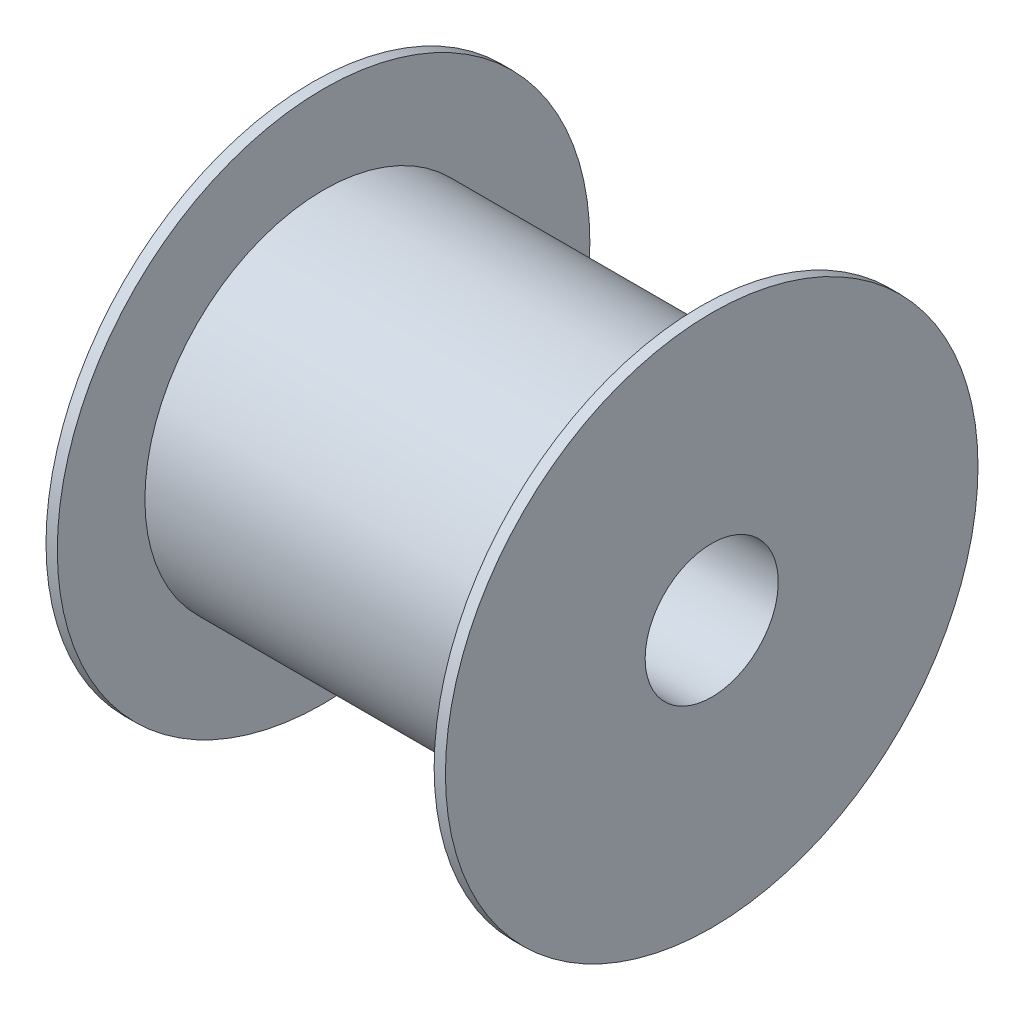
SolidWorks part; units mm, degrees
ref_plane "Front Plane" through (0, 0, 0) normal (0, 0, 1) x (1, 0, 0)
ref_plane "Top Plane" through (0, 0, 0) normal (0, 1, 0) x (1, 0, 0)
ref_plane "Right Plane" through (0, 0, 0) normal (1, 0, 0) x (0, 0, -1)
sketch "Sketch1" plane through (0, 0, 0) normal (0, 0, 1) x (1, 0, 0)
  line L0 (0, 0) -> (0, 10) construction
  line L1 (-30, 10) -> (30, 10)
  line L2 (30, 10) -> (30, 40)
  line L3 (30, 40) -> (28.3029, 40)
  line L4 (28.3029, 40) -> (28.3029, 26.8407)
  line L5 (28.3029, 26.8407) -> (-28.3029, 26.8407)
  line L6 (0, 26.8407) -> (0, 10) construction
  line L7 (-28.3029, 40) -> (-28.3029, 26.8407)
  line L8 (-30, 40) -> (-28.3029, 40)
  line L9 (-30, 10) -> (-30, 40)
  line L10 (0, 0) -> (59.9739, 0) construction
  dimension "D1" = 40
  dimension "D2" = 30
  dimension "D3" = 10
revolve "Revolve1" add sketch "Sketch1" angle 360 about L10
